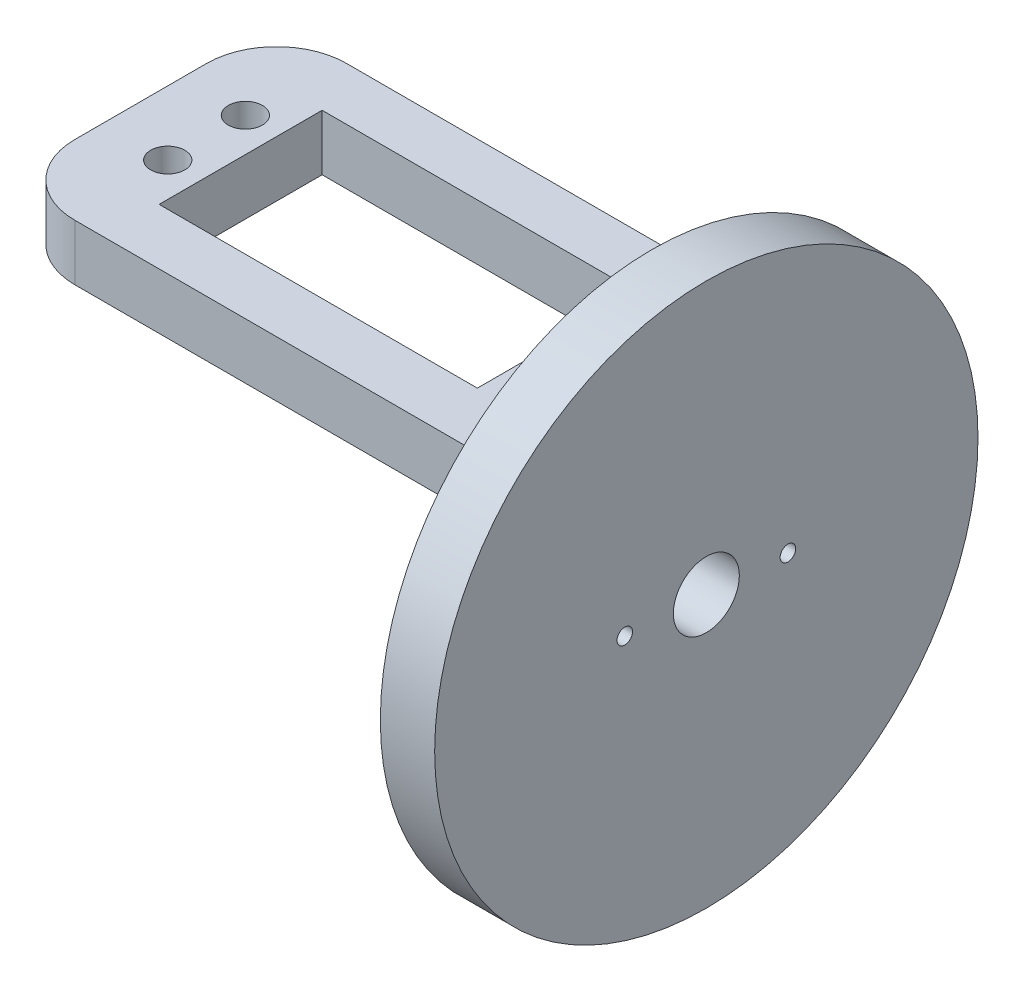
SolidWorks part; units mm, degrees
ref_plane "Front Plane" through (0, 0, 0) normal (0, 0, 1) x (1, 0, 0)
ref_plane "Top Plane" through (0, 0, 0) normal (0, 1, 0) x (1, 0, 0)
ref_plane "Right Plane" through (0, 0, 0) normal (1, 0, 0) x (0, 0, -1)
sketch "Sketch1" plane through (0, 0, 0) normal (0, 1, 0) x (1, 0, 0)
  line L1 (-47.8051, 16.632) -> (17.1949, 16.632)
  line L2 (-47.8051, 16.632) -> (-47.8051, -18.368)
  line L3 (-47.8051, -18.368) -> (17.1949, -18.368)
  line L4 (17.1949, 16.632) -> (17.1949, -18.368)
  point P4 (0, 0)
  point P5 (0, 0)
extrude "Boss-Extrude1" add sketch "Sketch1" along normal blind 7.2
fillet "Fillet1" radius 9 2 edges at (-47.8051, 3.6, 18.368) (-47.8051, 3.6, -16.632)
sketch "Sketch5" plane through (0, 7.2, 0) normal (0, 1, 0) x (1, 0, 0)
  circle A1 centre (-24.9358, -0.668) radius 2.25
  circle A2 centre (-28.9358, -0.6699) radius 0.8
  circle A3 centre (-20.9358, -0.6699) radius 0.8
extrude "Cut-Extrude1" cut sketch "Sketch5" against normal through all
sketch "Sketch7" plane through (17.1949, 0, 0) normal (1, 0, 0) x (0, 0, -1)
  circle A0 centre (0, -12.2514) radius 35
extrude "Boss-Extrude2" add sketch "Sketch7" along normal blind 7
sketch "Sketch8" plane through (17.1949, 0, 0) normal (-1, 0, 0) x (0, 0, 1)
  circle A0 centre (0, -12.2514) radius 4.25
  circle A1 centre (-10.5115, -12.8748) radius 1
  circle A2 centre (10.5115, -11.6281) radius 1
extrude "Cut-Extrude3" cut sketch "Sketch8" against normal up to next
sketch "Sketch9" plane through (0, 7.2, 0) normal (0, 1, 0) x (1, 0, 0)
  line L3 (-35.1358, 9.832) -> (5.8642, 9.832)
  line L4 (-35.1358, 9.832) -> (-35.1358, -11.168)
  line L5 (-35.1358, -11.168) -> (5.8642, -11.168)
  line L6 (5.8642, 9.832) -> (5.8642, -11.168)
  line L7 (-35.1358, 9.832) -> (5.8642, -11.168) construction
  line L8 (-35.1358, -11.168) -> (5.8642, 9.832) construction
  circle A0 centre (10.2572, 4.3249) radius 2.1922
  circle A1 centre (10.2538, -5.668) radius 2.2
  circle A2 centre (-39.5254, -5.668) radius 2.2
  circle A3 centre (-39.5254, 4.332) radius 2.2
  point P8 (-14.6358, -0.668)
extrude "Cut-Extrude4" cut sketch "Sketch9" against normal up to next
